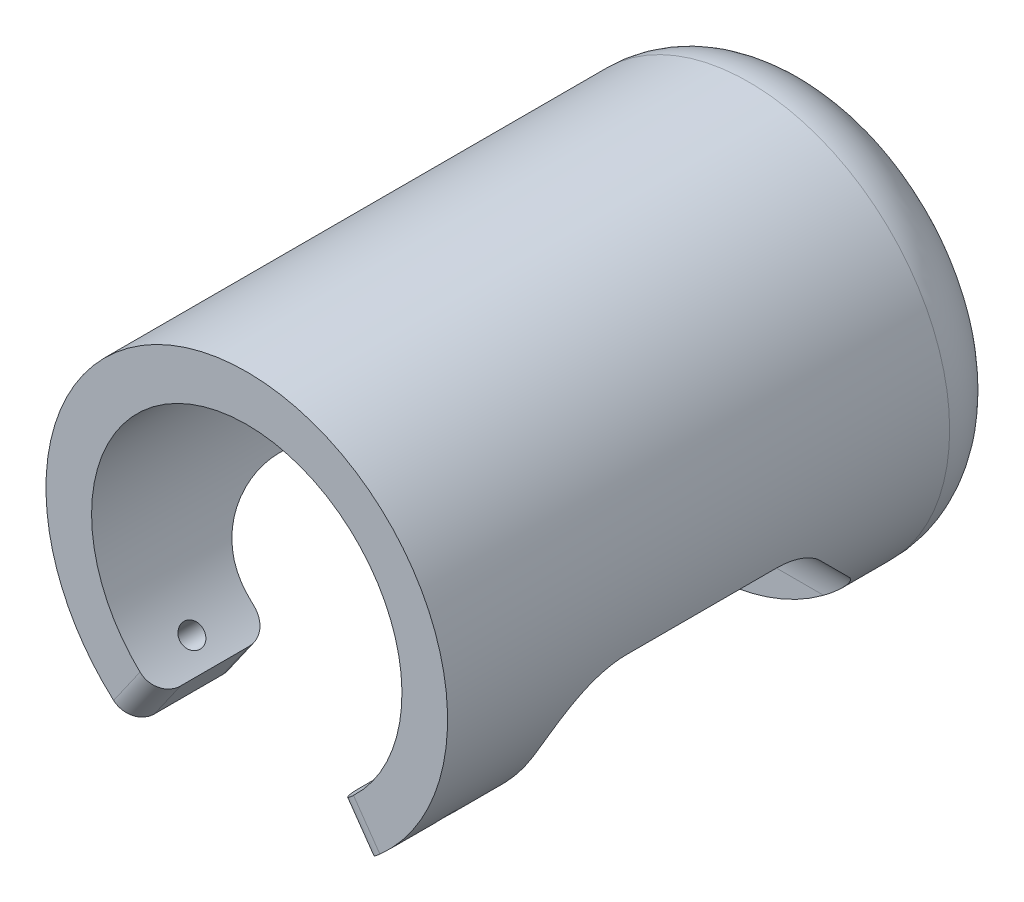
SolidWorks part; units mm, degrees
material "硅橡胶板 "
ref_plane "前视" through (0, 0, 0) normal (0, 0, 1) x (1, 0, 0)
ref_plane "上视" through (0, 0, 0) normal (0, 1, 0) x (1, 0, 0)
ref_plane "右视" through (0, 0, 0) normal (1, 0, 0) x (0, 0, -1)
sketch "草图1" plane through (0, 0, 0) normal (0, 0, 1) x (1, 0, 0)
  circle A0 centre (0, 0) radius 44
  circle A1 centre (0, 0) radius 41 construction
  dimension "D1" = 88
  dimension "D2" = 3
extrude "凸台-拉伸1" add sketch "草图1" along normal mid plane 125
fillet "圆角1" radius 15 1 edges at (44, 0, -62.5)
shell "抽壳1" thickness 10
sketch "草图2" plane through (0, 0, 0) normal (1, 0, 0) x (0, 0, -1)
  line L0 (0, 0) -> (-70.7678, 0) construction
  line L1 (-37.5, -44) -> (-37.5, -23)
  line L2 (-62.5, -44) -> (47.5, -44) construction
  line L3 (-22.5, -8) -> (10.2868, -8)
  line L5 (-62.5, 44) -> (-62.5, -44) construction
  line L6 (-37.5, -44) -> (37.5, -44)
  line L7 (37.5, -44) -> (37.5, -35.2132)
  line L8 (33.1066, -24.6066) -> (20.8934, -12.3934)
  arc A1 (-37.5, -23) -> (-22.5, -8) centre (-22.5, -23) cw
  arc A2 (10.2868, -8) -> (20.8934, -12.3934) centre (10.2868, -23) cw
  arc A3 (37.5, -35.2132) -> (33.1066, -24.6066) centre (22.5, -35.2132) ccw
  point P12 (16.5, -8)
  point P13 (-9.9784, -5)
  point P16 (-37.5, -8)
  point P20 (-37.5, -8)
  point P22 (37.5, -29)
  dimension "D5" = 15
  dimension "D6" = 15
  dimension "D9" = 15
  dimension "D1" = 25
  dimension "D2" = 8
  dimension "D3" = 100
  dimension "D4" = 45
  dimension "D7" = 0
  dimension "D8" = 15
extrude "切除-拉伸1" cut sketch "草图2" against normal through all both and the other way through all
sketch "草图3" plane through (0, 0, 62.5) normal (0, 0, 1) x (1, 0, 0)
  line L0 (0, 0) -> (0, -75.8405) construction
  line L1 (19.5016, -27.8512) -> (25.2374, -36.0427)
  line L2 (-19.5016, -27.8512) -> (-25.2374, -36.0427)
  circle A0 centre (0, 0) radius 44 construction
  circle A1 centre (0, 0) radius 34 construction
  arc A2 (-25.2374, -36.0427) -> (25.2374, -36.0427) centre (0, 0) ccw
  arc A3 (-19.5016, -27.8512) -> (19.5016, -27.8512) centre (0, 0) ccw
  dimension "D1" = 70
extrude "切除-拉伸2" cut sketch "草图3" against normal up to next
sketch "草图4" plane through (0, 0, 62.5) normal (0, 0, 1) x (1, 0, 0)
  circle A0 centre (0, 0) radius 25
  dimension "D1" = 50
extrude "切除-拉伸3" cut sketch "草图4" against normal through all
fillet "圆角2" radius 5 4 edges at (-22.3695, -31.9469, 37.5) (-22.3695, -31.9469, 62.5) (22.3695, -31.9469, 62.5) (22.3695, -31.9469, 37.5)
ref_plane "基准面2" through (0, 0, 50.5) normal (0, 0, 1) x (1, 0, 0)
sketch "草图6" plane through (0, 0, 50.5) normal (0, 0, 1) x (1, 0, 0)
  line L0 (0, -69.3583) -> (0, 0) construction
  line L1 (0, 0) -> (65.9954, -65.9954) construction
  line L2 (0, 0) -> (1.7678, 1.7678)
  line L3 (1.7678, 1.7678) -> (56.3134, -52.7779)
  line L4 (56.3134, -52.7779) -> (54.5457, -54.5457)
  line L5 (54.5457, -54.5457) -> (0, 0)
  dimension "D1" = 45
  dimension "D2" = 5
revolve "切除-旋转1" cut sketch "草图6" angle 360 about L1
mirror "镜向2" about plane through (0, 0, 0) normal (1, 0, 0) of "切除-旋转1"
